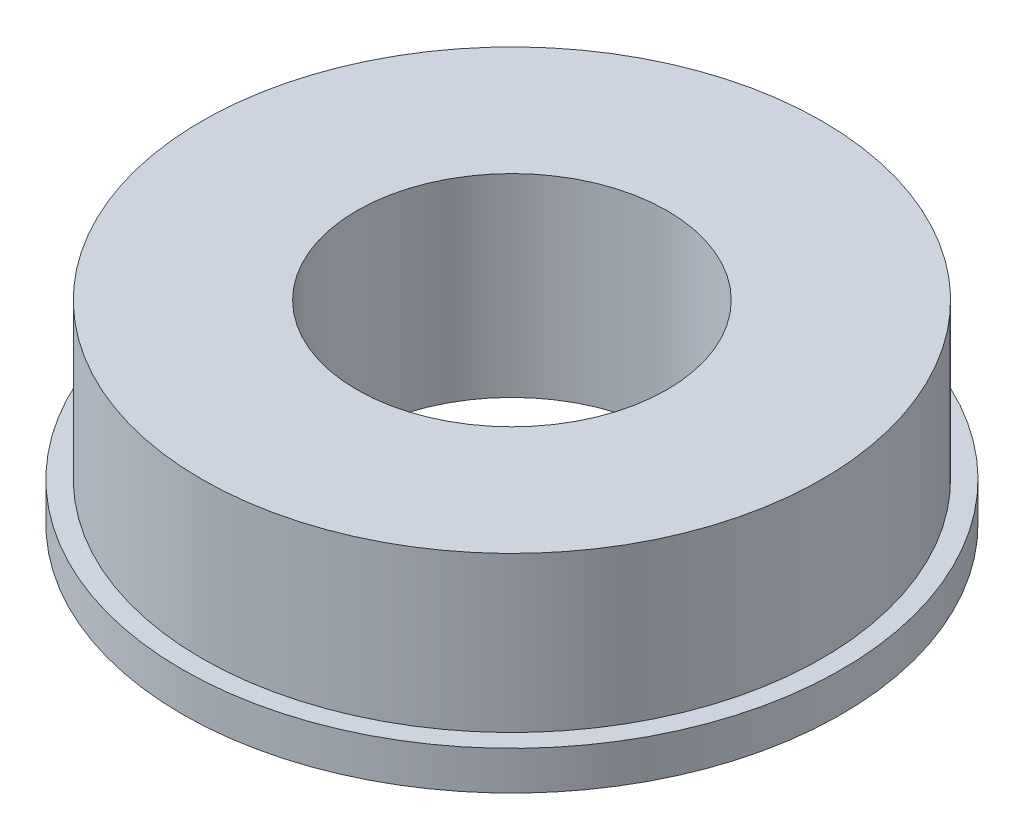
SolidWorks part; units mm, degrees
material "合金钢"
ref_plane "前视基准面" through (0, 0, 0) normal (0, 0, 1) x (1, 0, 0)
ref_plane "上视基准面" through (0, 0, 0) normal (0, 1, 0) x (1, 0, 0)
ref_plane "右视基准面" through (0, 0, 0) normal (1, 0, 0) x (0, 0, -1)
sketch "草图1" plane through (0, 0, 0) normal (0, 1, 0) x (1, 0, 0)
  circle A0 centre (0, 0) radius 8.5
  circle A1 centre (0, 0) radius 4
  dimension "D1" = 17
  dimension "D2" = 8
extrude "凸台-拉伸1" add sketch "草图1" along normal blind 1
sketch "草图2" plane through (0, 1, 0) normal (0, 1, 0) x (1, 0, 0)
  circle A0 centre (0, 0) radius 8
  circle A1 centre (0, 0) radius 4 construction
  circle A2 centre (0, 0) radius 4
  point P3 (0, 0)
  dimension "D1" = 16
extrude "凸台-拉伸2" add sketch "草图2" along normal blind 4
